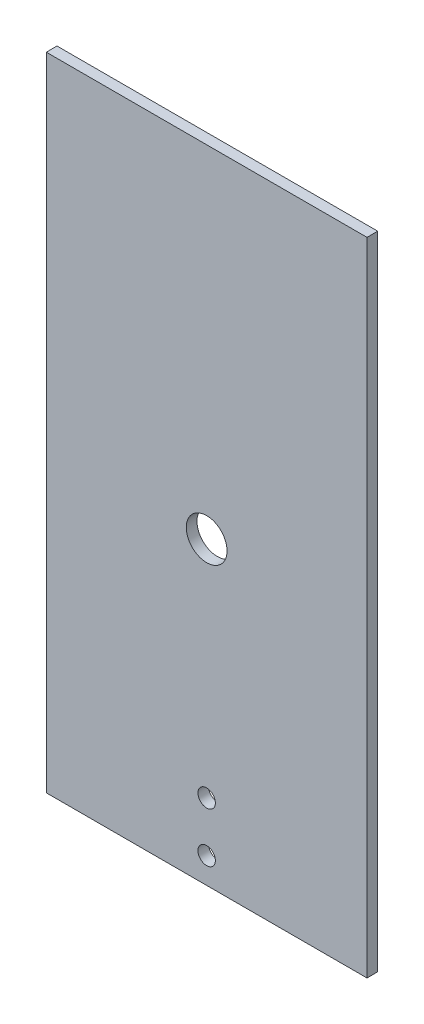
SolidWorks part; units mm, degrees
ref_plane "Front Plane" through (0, 0, 0) normal (0, 0, 1) x (1, 0, 0)
ref_plane "Top Plane" through (0, 0, 0) normal (0, 1, 0) x (1, 0, 0)
ref_plane "Right Plane" through (0, 0, 0) normal (1, 0, 0) x (0, 0, -1)
sketch "Sketch1" plane through (0, 0, 0) normal (0, 0, 1) x (1, 0, 0)
  line L0 (0, 42.672) -> (0, 25.8171) construction
  line L1 (30, 19.1606) -> (-30, 19.1606)
  line L2 (30, 19.1606) -> (30, 139.1606)
  line L3 (30, 139.1606) -> (-30, 139.1606)
  line L4 (-30, 19.1606) -> (-30, 139.1606)
  line L5 (3.4656, 19.1606) -> (-3.4656, 19.1606) construction
  point P4 (0, 139.1606)
  dimension "D1" = 120
  dimension "D2" = 60
extrude "Boss-Extrude1" add sketch "Sketch1" along normal blind 2
sketch "Sketch2" plane through (0, 0, 0) normal (0, 0, -1) x (-1, 0, 0)
  line L0 (-90.412, 75.261) -> (35.318, 75.261) construction
  line L1 (0, 19.1606) -> (0, 139.1606) construction
  line L2 (30, 19.1606) -> (-30, 19.1606) construction
  line L3 (-30, 139.1606) -> (30, 139.1606) construction
  circle A0 centre (0, 75.261) radius 3.8144
  point P0 (0, 75.261)
extrude "Cut-Extrude1" cut sketch "Sketch2" against normal blind 2
sketch "Sketch6" plane through (0, 0, 2) normal (0, 0, 1) x (1, 0, 0)
  point P0 (0, 33.332)
  point P1 (0, 23.992)
hole_wizard "#4 Clearance Hole2" positions "Sketch8" profile "Sketch7" hole size "#4" standard "Ansi Inch"
sketch "Sketch8" plane through (0, 0, 2) normal (0, 0, 1) x (1, 0, 0)
  point P1 (0, 33.332)
  point P4 (0, 23.992)
sketch "Sketch7" plane through (0, 33.332, 2) normal (1, 0, 0) x (0, -1, 0)
  line L0 (0, 0) -> (0, 10.9806)
  line L1 (0, 10.9806) -> (1.6319, 10)
  line L2 (1.6319, 10) -> (1.6319, 0)
  line L5 (1.6319, 0) -> (0, 0)
  line L10 (0, 10.9806) -> (-1.6319, 10) construction
  line L11 (0, -6.35) -> (0, 107.95) construction
  dimension "Hole Dia." = 3.2639
  dimension "Hole Depth" = 10
  dimension "Drill Angle" = 118
